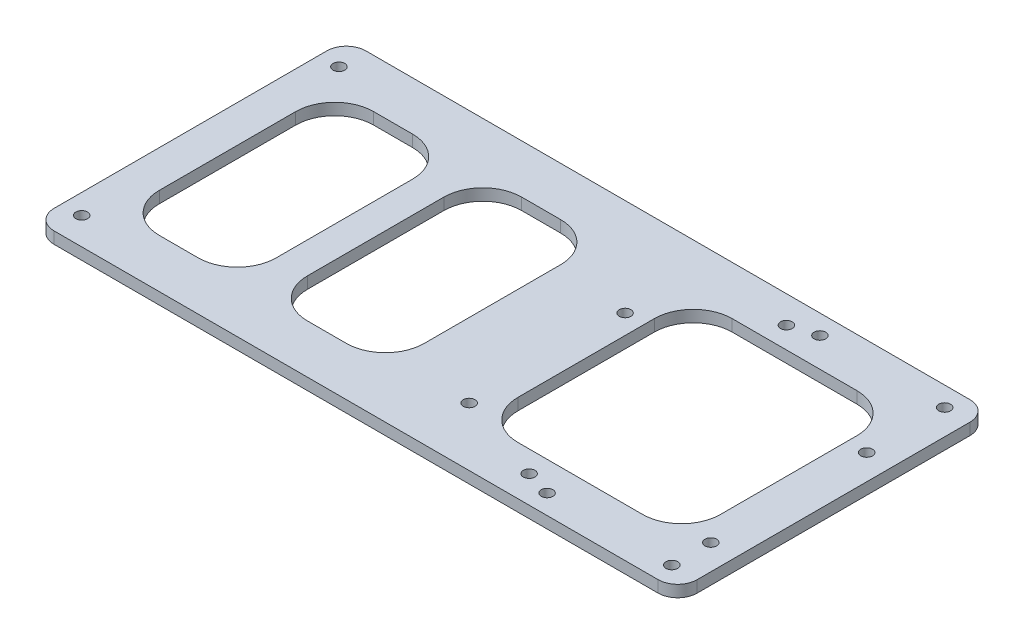
SolidWorks part; units mm, degrees
material "Thornel Mat VMA"
ref_plane "前视基准面" through (0, 0, 0) normal (0, 0, 1) x (1, 0, 0)
ref_plane "上视基准面" through (0, 0, 0) normal (0, 1, 0) x (1, 0, 0)
ref_plane "右视基准面" through (0, 0, 0) normal (1, 0, 0) x (0, 0, -1)
other "Configuration Table"
sketch "草图1" plane through (0, 0, 0) normal (0, 1, 0) x (1, 0, 0)
  line L0 (0, 0) -> (0, 35.173) construction
  line L1 (-37.5, -35) -> (37.5, -35)
  line L2 (-37.5, -35) -> (-37.5, 35)
  line L3 (-37.5, 35) -> (37.5, 35)
  line L4 (37.5, -35) -> (37.5, 35)
  line L5 (-37.5, -35) -> (37.5, 35) construction
  line L6 (-37.5, 35) -> (37.5, -35) construction
  line L7 (0, 0) -> (-43.4462, 0) construction
  line L8 (-37.5, 35) -> (-127.5, 35)
  line L9 (-127.5, 35) -> (-127.5, -35)
  line L10 (-127.5, -35) -> (-37.5, -35)
  line L11 (-127.5, 35) -> (-127.5, 45)
  line L12 (-127.5, 45) -> (37.5, 45)
  line L13 (37.5, 45) -> (37.5, 35)
  line L14 (-65, 0) -> (-65, 58.3463) construction
  line L15 (-65, 5) -> (-116.5975, 5) construction
  line L16 (-65, 5) -> (96.0266, 5) construction
  line L17 (-80, -22.5) -> (-50, -22.5)
  line L18 (-80, -22.5) -> (-80, 32.5)
  line L19 (-80, 32.5) -> (-50, 32.5)
  line L20 (-50, -22.5) -> (-50, 32.5)
  line L21 (-80, -22.5) -> (-50, 32.5) construction
  line L22 (-80, 32.5) -> (-50, -22.5) construction
  line L23 (15, 5) -> (15, 63.1511) construction
  line L25 (-26, -22.5) -> (26, -22.5)
  line L26 (-26, -22.5) -> (-26, 32.5)
  line L27 (-26, 32.5) -> (26, 32.5)
  line L28 (26, -22.5) -> (26, 32.5)
  line L29 (-26, -22.5) -> (26, 32.5) construction
  line L30 (-26, 32.5) -> (26, -22.5) construction
  line L31 (-118, -22.5) -> (-88, -22.5)
  line L32 (-118, -22.5) -> (-118, 32.5)
  line L33 (-118, 32.5) -> (-88, 32.5)
  line L34 (-88, -22.5) -> (-88, 32.5)
  line L35 (-118, -22.5) -> (-88, 32.5) construction
  line L36 (-118, 32.5) -> (-88, -22.5) construction
  circle A0 centre (-31, 20) radius 1.5
  circle A1 centre (-31, -20) radius 1.5
  circle A2 centre (31, -20) radius 1.5
  circle A3 centre (31, 20) radius 1.5
  circle A4 centre (-122.4, 38) radius 1.5
  circle A7 centre (-7.6, 38) radius 1.5
  circle A8 centre (-7.6, -28) radius 1.5
  circle A9 centre (-122.4, -28) radius 1.5
  circle A10 centre (31, 40) radius 1.5
  circle A11 centre (31, -30) radius 1.5
  circle A12 centre (-1, -30) radius 1.5
  circle A13 centre (-1, 40) radius 1.5
  point P0 (0, 0)
  point P33 (-65, 5)
  point P49 (0, 5)
  point P54 (-103, 5)
  dimension "D3" = 3
  dimension "D4" = 40
  dimension "D5" = 62
  dimension "D8" = 3
  dimension "D9" = 114.8
  dimension "D10" = 66
  dimension "D16" = 3
  dimension "D17" = 32
  dimension "D18" = 70
  dimension "D1" = 75
  dimension "D2" = 70
  dimension "D6" = 90
  dimension "D7" = 10
  dimension "D11" = 5
  dimension "D12" = 65
  dimension "D13" = 30
  dimension "D14" = 15
  dimension "D15" = 55
  dimension "D19" = 15
  dimension "D20" = 52
  dimension "D21" = 55
  dimension "D22" = 30
  dimension "D23" = 8
  dimension "D24" = 55
extrude "凸台-拉伸1" add sketch "草图1" along normal blind 3 contours L9 L10 L2 L8 | L1 L4 L3 L2 A1 A0 A2 A3 | L13 L12 L11 L8 L3
fillet "圆角1" radius 10 8 edges at (-80, 1.5, 22.5) (-50, 1.5, 22.5) (-50, 1.5, -32.5) (-80, 1.5, -32.5) (-118, 1.5, 22.5) (-88, 1.5, 22.5) (-88, 1.5, -32.5) (-118, 1.5, -32.5)
fillet "圆角2" radius 5 4 edges at (37.5, 1.5, 35) (37.5, 1.5, -45) (-127.5, 1.5, -45) (-127.5, 1.5, 35)
fillet "圆角3" radius 10 4 edges at (-26, 1.5, 22.5) (26, 1.5, 22.5) (26, 1.5, -32.5) (-26, 1.5, -32.5)
